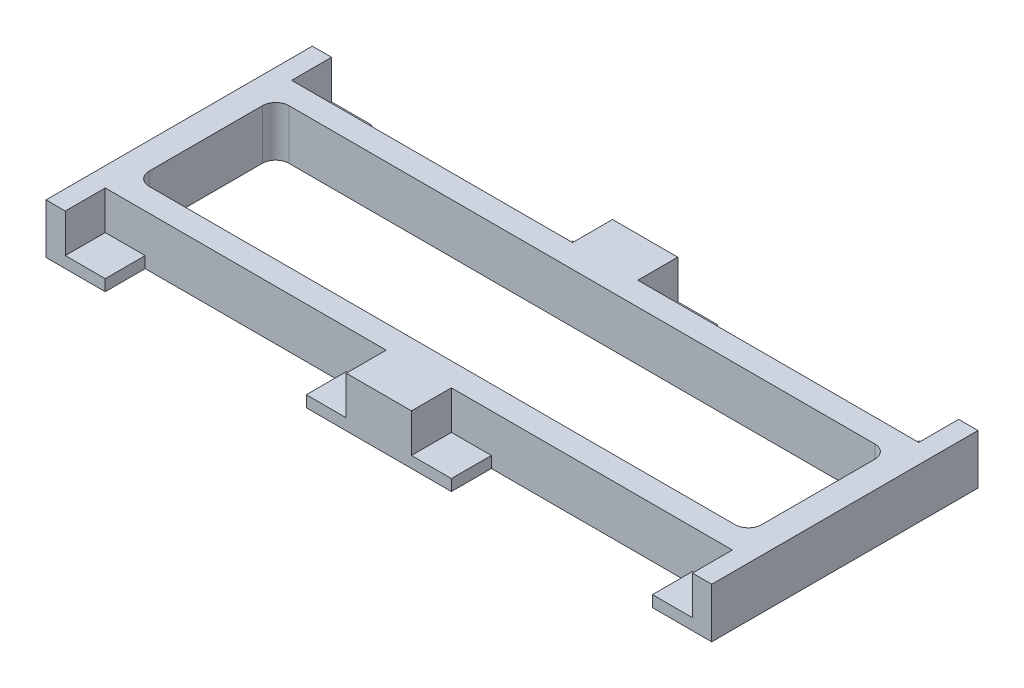
SolidWorks part; units mm, degrees
ref_plane "Front Plane" through (0, 0, 0) normal (0, 0, 1) x (1, 0, 0)
ref_plane "Top Plane" through (0, 0, 0) normal (0, 1, 0) x (1, 0, 0)
ref_plane "Right Plane" through (0, 0, 0) normal (1, 0, 0) x (0, 0, -1)
sketch "Sketch2" plane through (0, 0, 0) normal (0, 1, 0) x (1, 0, 0)
  line L1 (-250, -50) -> (250, -50)
  line L2 (-250, -50) -> (-250, 150)
  line L3 (-250, 150) -> (250, 150)
  line L4 (250, -50) -> (250, 150)
  point P0 (0, 0)
  dimension "D1" = 500
  dimension "D2" = 200
extrude "Boss-Extrude1" add sketch "Sketch2" along normal blind 37.5
sketch "Sketch5" plane through (0, 0, -150) normal (0, 0, -1) x (-1, 0, 0)
  line L5 (24.5, 66.5) -> (54.5, 66.5)
  line L6 (54.5, 66.5) -> (54.5, 75)
  line L7 (-250, 0) -> (250, 0) construction
  line L17 (54.5, 75) -> (205.5, 75)
  line L18 (205.5, 75) -> (205.5, 66.5)
  line L19 (205.5, 66.5) -> (235.5, 66.5)
  line L20 (235.5, 66.5) -> (235.5, 8.5)
  line L21 (235.5, 8.5) -> (205.5, 8.5)
  line L22 (205.5, 8.5) -> (205.5, 0)
  line L23 (205.5, 0) -> (54.5, 0)
  line L24 (54.5, 0) -> (54.5, 8.5)
  line L25 (54.5, 8.5) -> (24.5, 8.5)
  line L26 (24.5, 8.5) -> (24.5, 66.5)
  line L27 (54.5, 75) -> (205.5, 0) construction
  line L28 (205.5, 75) -> (54.5, 0) construction
  line L31 (250, 37.5) -> (250, 0) construction
  point P18 (130, 37.5)
  dimension "D1" = 151
  dimension "D2" = 8.5
  dimension "D3" = 0
  dimension "D4" = 30
  dimension "D5" = 30
  dimension "D7" = 120
  dimension "D8" = 37.5
extrude "Cut-Extrude3" cut sketch "Sketch5" against normal blind 30
ref_plane "Plane1" through (0, 0, -50) normal (0, 0, 1) x (1, 0, 0)
pattern_linear "LPattern1" count 2 spacing 260 along (1, 0, 0) of "Cut-Extrude3"
mirror "Mirror1" about plane through (0, 0, -50) normal (0, 0, 1) of "LPattern1", "Cut-Extrude3"
sketch "Sketch7" plane through (0, 37.5, 0) normal (0, 1, 0) x (1, 0, 0)
  line L0 (-20.625, 50) -> (20.625, 50) construction
  line L1 (-230, -2.5) -> (230, -2.5)
  line L2 (-230, -2.5) -> (-230, 102.5)
  line L3 (-230, 102.5) -> (230, 102.5)
  line L4 (230, -2.5) -> (230, 102.5)
  line L5 (-230, -2.5) -> (230, 102.5) construction
  line L6 (-230, 102.5) -> (230, -2.5) construction
  line L7 (0, -20.625) -> (0, 20.625) construction
  point P0 (0, 50)
  dimension "D1" = 460
  dimension "D2" = 105
extrude "Cut-Extrude4" cut sketch "Sketch7" against normal blind 160
fillet "Fillet1" radius 10 1 edges at (-230, 18.75, -102.5)
fillet "Fillet2" radius 10 1 edges at (-230, 18.75, 2.5)
fillet "Fillet3" radius 10 1 edges at (230, 18.75, -102.5)
fillet "Fillet4" radius 10 1 edges at (230, 18.75, 2.5)
